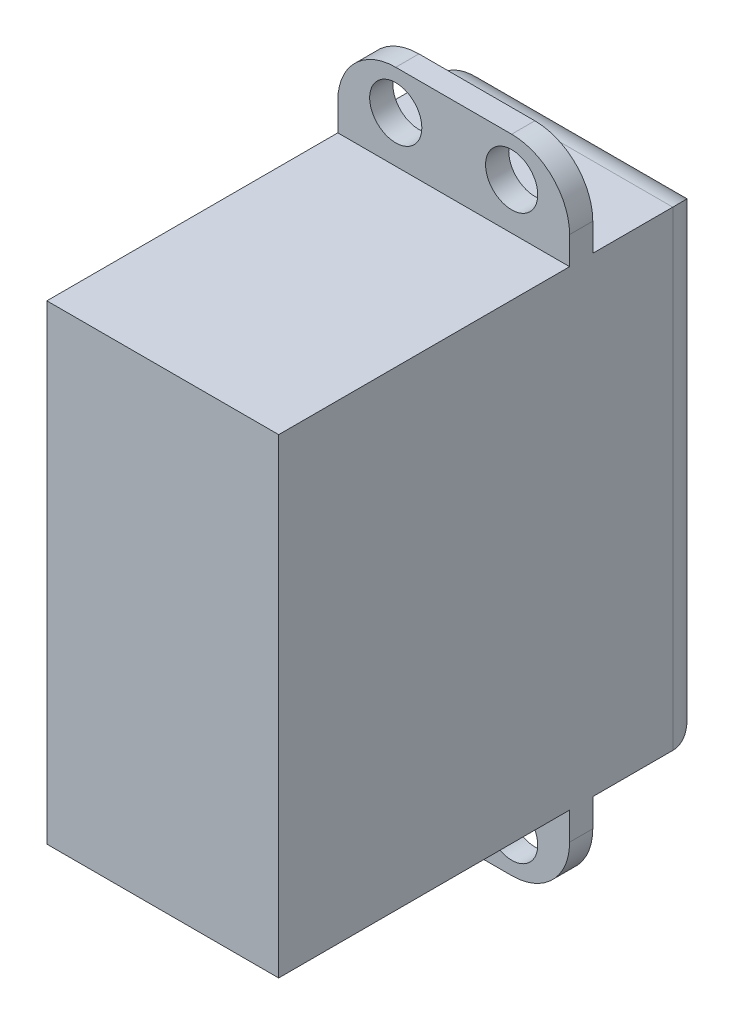
SolidWorks part; units mm, degrees
ref_plane "Front Plane" through (0, 0, 0) normal (0, 0, 1) x (1, 0, 0)
ref_plane "Top Plane" through (0, 0, 0) normal (0, 1, 0) x (1, 0, 0)
ref_plane "Right Plane" through (0, 0, 0) normal (1, 0, 0) x (0, 0, -1)
sketch "Sketch1" plane through (0, 0, 0) normal (0, 0, 1) x (1, 0, 0)
  line L0 (0, 27.7) -> (0, -27.7) construction
  line L1 (-5, -27.7) -> (5, -27.7)
  line L2 (-10, -22.7) -> (-10, 22.7)
  line L3 (-5, 27.7) -> (5, 27.7)
  line L4 (10, -22.7) -> (10, 22.7)
  line L5 (-10, -27.7) -> (10, 27.7) construction
  line L6 (-10, 27.7) -> (10, -27.7) construction
  line L7 (-10, 0) -> (10, 0) construction
  line L8 (-10, 20.3) -> (10, 20.3) construction
  line L9 (-10, -20.3) -> (10, -20.3) construction
  arc A0 (-5, -27.7) -> (-10, -22.7) centre (-5, -22.7) cw
  arc A1 (5, -27.7) -> (10, -22.7) centre (5, -22.7) ccw
  arc A2 (10, 22.7) -> (5, 27.7) centre (5, 22.7) ccw
  arc A3 (-10, 22.7) -> (-5, 27.7) centre (-5, 22.7) cw
  circle A4 centre (0, 9.8) radius 2.8365
  circle A5 centre (-5, 24.3) radius 2.25
  circle A6 centre (5, 24.3) radius 2.25
  circle A7 centre (5, -24.3) radius 2.25
  circle A8 centre (-5, -24.3) radius 2.25
  point P0 (0, 0)
  dimension "D3" = 5
  dimension "D4" = 4.5
  dimension "D6" = 48.6
  dimension "D1" = 20
  dimension "D2" = 55.4
  dimension "D5" = 10
  dimension "D7" = 14.5
  dimension "D8" = 40.6
sketch "Sketch2" plane through (0, 0, 0) normal (0, 0, 1) x (1, 0, 0)
  line L1 (-10, 20.3) -> (10, 20.3)
  line L2 (-10, 20.3) -> (-10, -20.3)
  line L3 (-10, -20.3) -> (10, -20.3)
  line L4 (10, 20.3) -> (10, -20.3)
extrude "Boss-Extrude1" add sketch "Sketch2" along normal blind 27.1 and the other way blind 9.9
extrude "Boss-Extrude2" add sketch "Sketch1" along normal blind 2
fillet "Fillet1" radius 3 4 edges at (0, 20.3, -9.9) (0, -20.3, -9.9) (10, 0, -9.9) (-10, 0, -9.9)
sketch "Sketch3" plane through (0, 0, -9.9) normal (0, 0, -1) x (-1, 0, 0)
  circle A0 centre (0, 9.8) radius 3
  point P2 (5, 24.3)
  dimension "D1" = 6
  dimension "D2" = 14.5
extrude "Boss-Extrude3" add sketch "Sketch3" along normal blind 5
